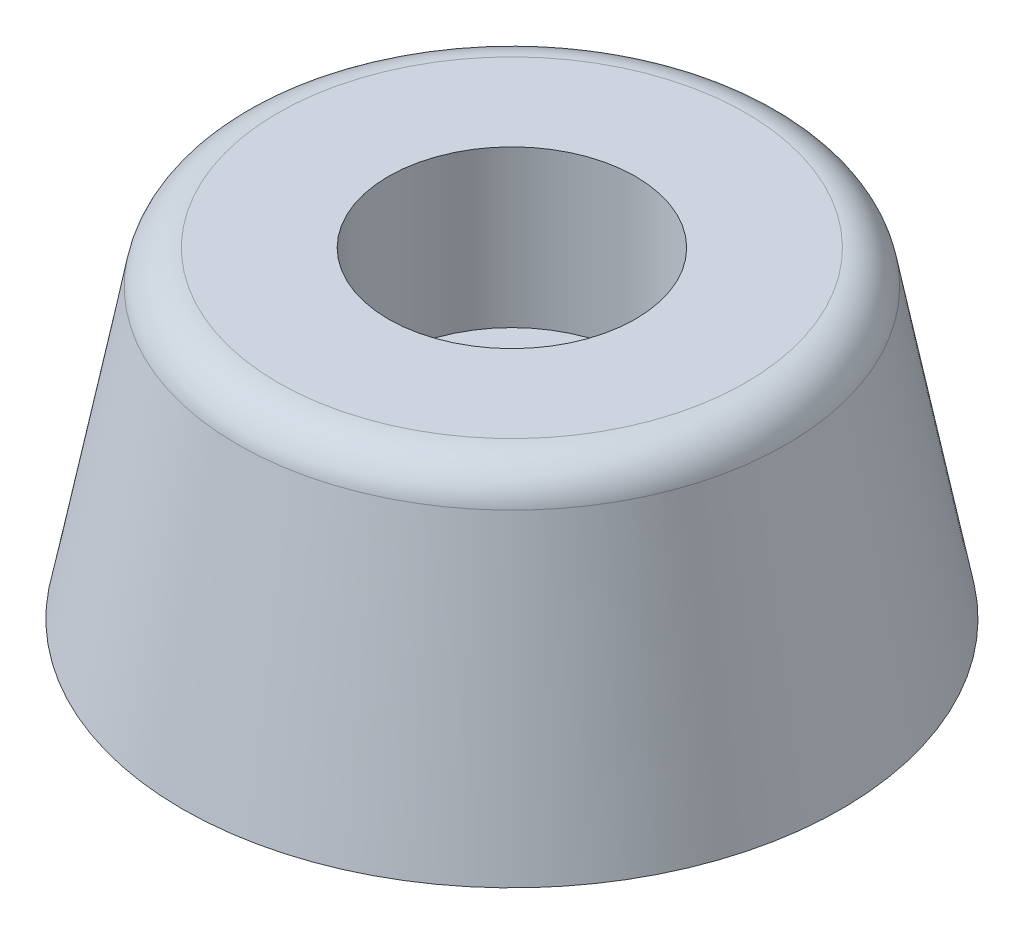
SolidWorks part; units mm, degrees
material "Rubber"
ref_plane "Front Plane" through (0, 0, 0) normal (0, 0, 1) x (1, 0, 0)
ref_plane "Top Plane" through (0, 0, 0) normal (0, 1, 0) x (1, 0, 0)
ref_plane "Right Plane" through (0, 0, 0) normal (1, 0, 0) x (0, 0, -1)
sketch "Skica1" plane through (0, 0, 0) normal (0, 0, 1) x (1, 0, 0)
  line L0 (0, 16.1707) -> (0, 0) construction
  line L1 (-1.5, 0) -> (-8, 0)
  line L2 (-8, 0) -> (-6.5, 7.8)
  line L3 (-6.5, 7.8) -> (-3, 7.8)
  line L4 (-3, 7.8) -> (-3, 4)
  line L5 (-3, 4) -> (-1.5, 4)
  line L6 (-1.5, 4) -> (-1.5, 0)
  dimension "D1" = 3
  dimension "D2" = 6
  dimension "D3" = 16
  dimension "D4" = 13
  dimension "D5" = 4
  dimension "D6" = 7.8
revolve "Rotovat1" add sketch "Skica1" angle 360 about L0
fillet "Zaoblit1" radius 1 1 edges at (0, 7.8, 6.5)
